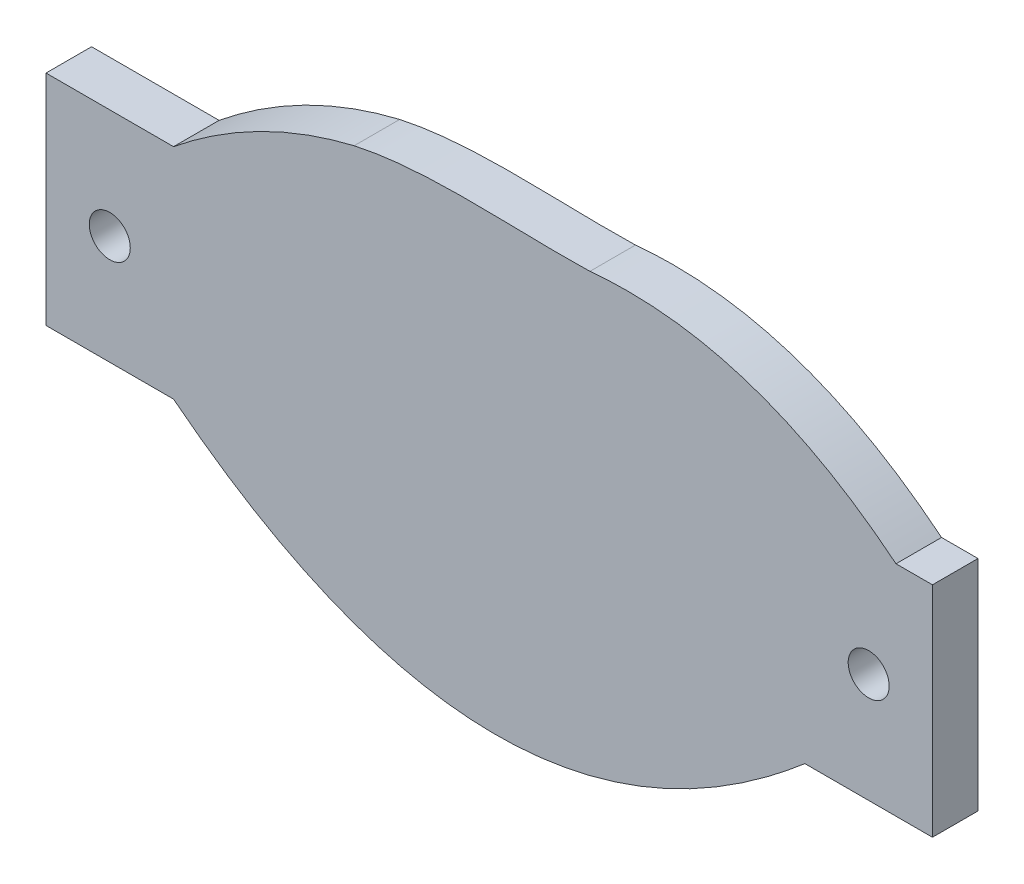
SolidWorks part; units mm, degrees
material "Papel canelado"
ref_plane "Plano frontal" through (0, 0, 0) normal (0, 0, 1) x (1, 0, 0)
ref_plane "Plano superior" through (0, 0, 0) normal (0, 1, 0) x (1, 0, 0)
ref_plane "Plano direito" through (0, 0, 0) normal (1, 0, 0) x (0, 0, -1)
sketch "Esboço1" plane through (0, 0, 0) normal (0, 0, 1) x (1, 0, 0)
  line L0 (-1000, 0) -> (49000, 0) construction
  line L1 (7, 12) -> (-7, 12)
  line L3 (7, -12) -> (-7, -12)
  line L4 (-7, 12) -> (-7, -12)
  line L5 (7, 12) -> (-7, -12) construction
  line L6 (7, -12) -> (-7, 12) construction
  line L7 (90.3, 12) -> (86.3, 12)
  line L8 (90.3, 12) -> (90.3, -12)
  line L9 (90.3, -12) -> (76.3, -12)
  line L11 (90.3, 12) -> (76.3, -12) construction
  line L12 (90.3, -12) -> (86.3, 12) construction
  line L13 (7, 12) -> (86.3, 12) construction
  line L14 (46.65, 0) -> (46.65, 23) construction
  line L15 (46.65, 0) -> (46.65, -26) construction
  line L16 (46.65, 23) -> (7, 23) construction
  line L17 (26.825, 22) -> (26.825, 0) construction
  line L18 (46.65, 23) -> (86.3, 23) construction
  line L19 (66.475, 23) -> (66.475, 12) construction
  line L20 (66.475, 17.5) -> (46.65, 17.5) construction
  line L21 (56.5625, 23.2) -> (56.5625, 0) construction
  circle A0 centre (0, 0) radius 2.25
  circle A1 centre (83.3, 0) radius 2.25
  spline S0 degree 2 poles (7, 12) (16.153, 19.4342) (26.825, 22) knots 0 0 0 0.533499 0.533499 0.533499
  spline S1 degree 2 poles (7, -12) (43.0974, -40.4353) (76.3, -12) knots 0 0 0 1 1 1
  spline S2 degree 3 poles (26.825, 22) (35.1807, 23.8295) (44.0924, 22.7789) (52.7028, 23) knots 0 0 0 0 0.489997 0.489997 0.489997 0.489997
  spline S3 degree 2 poles (52.7028, 23) (70.6211, 24.7033) (86.3, 12) knots 0 0 0 1 1 1
  point P0 (0, 0)
  point P6 (87.1889, 6.6667)
  point P19 (46.65, 12)
  point P33 (0, 0)
  dimension "D2" = 4.5
  dimension "D1" = 14
  dimension "D3" = 97.3
  dimension "D4" = 23
  dimension "D5" = 24
  dimension "D6" = 26
  dimension "D7" = 22
  dimension "D8" = 23.2
extrude "Ressalto-extrusão1" add sketch "Esboço1" along normal blind 5
